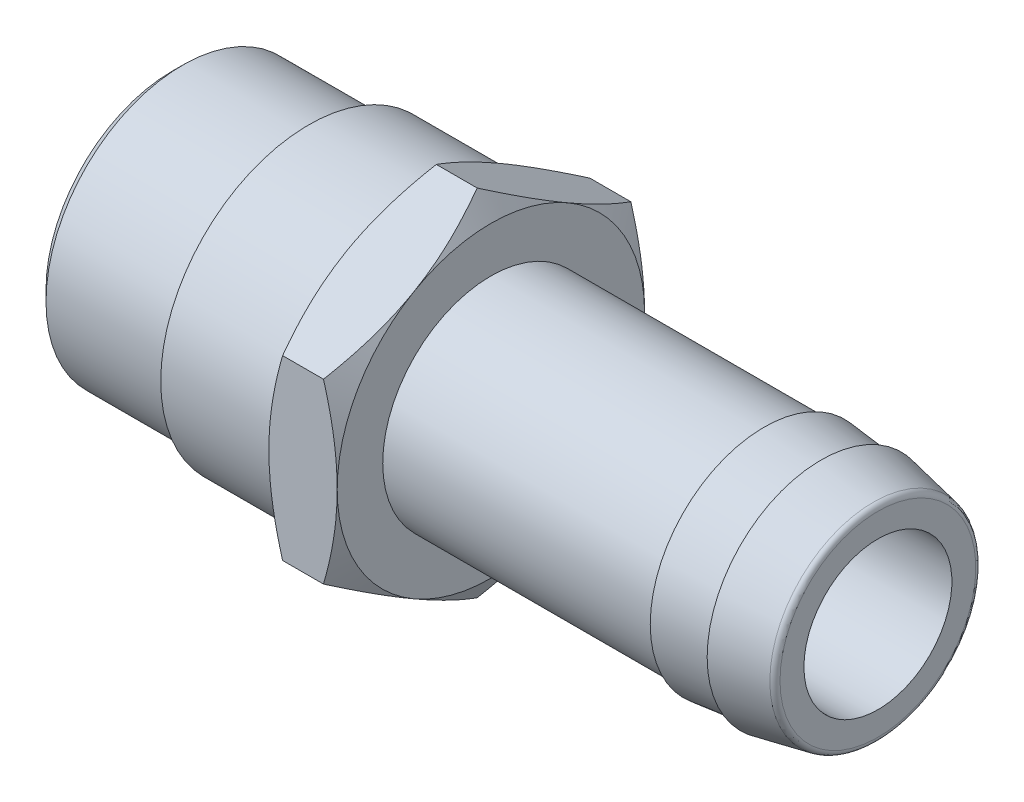
SolidWorks part; units mm, degrees
ref_plane "Płaszczyzna przednia" through (0, 0, 0) normal (0, 0, 1) x (1, 0, 0)
ref_plane "Płaszczyzna górna" through (0, 0, 0) normal (0, 1, 0) x (1, 0, 0)
ref_plane "Płaszczyzna prawa" through (0, 0, 0) normal (1, 0, 0) x (0, 0, -1)
sketch "Szkic1" plane through (0, 0, 0) normal (0, 0, 1) x (1, 0, 0)
  line L0 (0, 0) -> (0, 11.08)
  line L1 (0, 11.08) -> (0.92, 12)
  line L2 (0.92, 12) -> (12, 12)
  line L3 (12, 12) -> (12, 0)
  line L4 (12, 0) -> (0, 0)
  line L5 (12, 0) -> (0, 0) construction
revolve "Obrót1" add sketch "Szkic1" angle 360 about L5
sketch "Szkic2" plane through (0, 0, 0) normal (0, 0, 1) x (1, 0, 0)
  line L0 (12, 0) -> (12, 13)
  line L1 (12, 13) -> (22, 13)
  line L2 (22, 13) -> (22, 0)
  line L3 (22, 0) -> (12, 0)
  line L4 (22, 0) -> (12, 0) construction
revolve "Obrót2" add sketch "Szkic2" angle 360 about L4
ref_plane "Płaszczyzna1" through (22, 0, 0) normal (1, 0, 0) x (0, 0, -1)
sketch "Szkic3" plane through (22, 0, 0) normal (1, 0, 0) x (0, 0, -1)
  line L0 (-13.5, 7.7942) -> (-13.5, -7.7942)
  line L1 (-13.5, -7.7942) -> (0, -15.5885)
  line L2 (0, -15.5885) -> (13.5, -7.7942)
  line L3 (13.5, -7.7942) -> (13.5, 7.7942)
  line L4 (13.5, 7.7942) -> (0, 15.5885)
  line L5 (0, 15.5885) -> (-13.5, 7.7942)
extrude "Dodanie-wyciągnięcie1" add sketch "Szkic3" along normal blind 6
sketch "Szkic4" plane through (0, 0, 0) normal (0, 0, 1) x (1, 0, 0)
  line L0 (28, 0) -> (28, 9.5)
  line L1 (28, 9.5) -> (52, 9.5)
  line L2 (52, 9.5) -> (52, 0)
  line L3 (52, 0) -> (28, 0)
  line L4 (52, 0) -> (28, 0) construction
revolve "Obrót3" add sketch "Szkic4" angle 360 about L4
sketch "Szkic5" plane through (0, 0, 0) normal (0, 0, 1) x (1, 0, 0)
  line L0 (52, 0) -> (52, 10)
  line L1 (52, 10) -> (57, 9.5)
  line L2 (57, 9.5) -> (57, 10)
  line L3 (57, 10) -> (61.597, 9.0905)
  line L4 (62, 8.6) -> (62, 0)
  line L5 (62, 0) -> (52, 0)
  line L6 (62, 0) -> (52, 0) construction
  arc A0 (61.597, 9.0905) -> (62, 8.6) centre (61.5, 8.6) cw
revolve "Obrót4" add sketch "Szkic5" angle 360 about L6
sketch "Szkic6" plane through (0, 0, 0) normal (0, 0, 1) x (1, 0, 0)
  line L0 (0, 0) -> (0, 7.2071)
  line L1 (0, 7.2071) -> (0.7071, 6.5)
  line L2 (0.7071, 6.5) -> (62, 6.5)
  line L3 (62, 6.5) -> (62, 0)
  line L4 (62, 0) -> (0, 0)
  line L5 (62, 0) -> (0, 0) construction
revolve "Wycięcie-obrót1" cut sketch "Szkic6" angle 360 about L5
sketch "Szkic7" plane through (0, 0, 0) normal (0, 0, 1) x (1, 0, 0)
  line L0 (22, 13.5) -> (29.7942, 27)
  line L1 (29.7942, 27) -> (22, 27)
  line L2 (22, 27) -> (22, 13.5)
  line L3 (22, 0) -> (0, 0) construction
revolve "Wycięcie-obrót2" cut sketch "Szkic7" angle 360 about L3
sketch "Szkic8" plane through (0, 0, 0) normal (0, 0, 1) x (1, 0, 0)
  line L0 (20.2058, 27) -> (28, 13.5)
  line L1 (28, 13.5) -> (28, 27)
  line L2 (28, 27) -> (20.2058, 27)
  line L3 (22, 0) -> (0, 0) construction
revolve "Wycięcie-obrót3" cut sketch "Szkic8" angle 360 about L3
